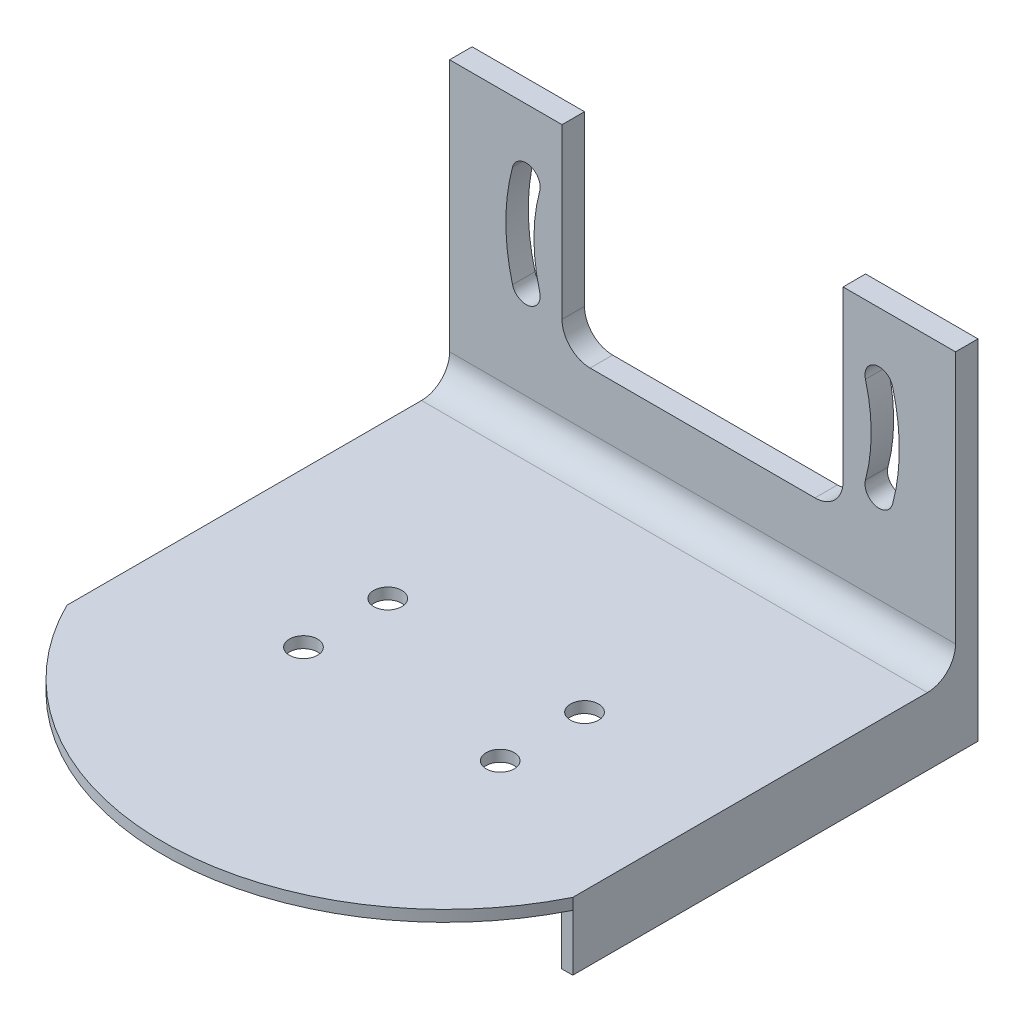
SolidWorks part; units mm, degrees
ref_plane "Front Plane" through (0, 0, 0) normal (0, 0, 1) x (1, 0, 0)
ref_plane "Top Plane" through (0, 0, 0) normal (0, 1, 0) x (1, 0, 0)
ref_plane "Right Plane" through (0, 0, 0) normal (1, 0, 0) x (0, 0, -1)
sketch "Sketch1" plane through (0, 0, 0) normal (0, 1, 0) x (1, 0, 0)
  line L1 (100, 50) -> (-100, 50)
  line L2 (100, 50) -> (100, -50)
  line L3 (100, -50) -> (-100, -50)
  line L4 (-100, 50) -> (-100, -50)
  line L5 (100, 50) -> (-100, -50) construction
  line L6 (100, -50) -> (-100, 50) construction
  point P0 (0, 0)
extrude "Boss-Extrude1" add sketch "Sketch1" along normal blind 2
sketch "Sketch3" plane through (0, 2, 0) normal (0, 1, 0) x (1, 0, 0)
  line L0 (0, 50) -> (-45, 50)
  line L1 (100, 50) -> (-100, 50) construction
  line L2 (0, 50) -> (45, 50)
  line L3 (45, 50) -> (45, 46)
  line L4 (-45, 50) -> (-45, 46)
  line L5 (-45, 46) -> (45, 46)
extrude "Boss-Extrude2" add sketch "Sketch3" along normal blind 50
sketch "Sketch4" plane through (0, 0, -50) normal (0, 0, -1) x (-1, 0, 0)
  line L0 (-45, 52) -> (-25, 52) construction
  line L1 (-45, 52) -> (45, 52) construction
  line L2 (45, 52) -> (25, 52) construction
  line L3 (25, 52) -> (25, 22)
  line L5 (-25, 22) -> (-25, 52)
  line L6 (-25, 52) -> (25, 52)
  line L7 (20, 17) -> (-20, 17)
  line L11 (25, 52) -> (-25, 52)
  arc A0 (-20, 17) -> (-25, 22) centre (-20, 22) cw
  arc A1 (20, 17) -> (25, 22) centre (20, 22) ccw
  dimension "D1" = 5
extrude "Cut-Extrude6" cut sketch "Sketch4" against normal blind 50
sketch "Sketch5" plane through (0, 0, -50) normal (0, 0, -1) x (-1, 0, 0)
  line L0 (-25, 52) -> (0, 52) construction
  line L1 (0, 52) -> (0, 32) construction
  line L2 (0, 32) -> (-17.2464, 32) construction
  line L3 (0, 32) -> (-28.9778, 39.7646) construction
  line L4 (-33.8074, 41.0587) -> (-39.8806, 42.686) construction
  arc A0 (-28.9778, 39.7646) -> (-28.9778, 24.2354) centre (0, 32) ccw
  arc A1 (-33.8074, 41.0587) -> (-33.8074, 22.9413) centre (0, 32) ccw
  arc A2 (-28.9778, 39.7646) -> (-33.8074, 41.0587) centre (-31.3926, 40.4116) ccw
  arc A3 (-28.9778, 24.2354) -> (-33.8074, 22.9413) centre (-31.3926, 23.5884) cw
  arc A4 (28.9778, 24.2354) -> (33.8074, 22.9413) centre (31.3926, 23.5884) ccw
  arc A5 (28.9778, 39.7646) -> (33.8074, 41.0587) centre (31.3926, 40.4116) cw
  arc A6 (28.9778, 24.2354) -> (28.9778, 39.7646) centre (0, 32) ccw
  arc A7 (33.8074, 22.9413) -> (33.8074, 41.0587) centre (0, 32) ccw
  dimension "D1" = 15
extrude "Cut-Extrude7" cut sketch "Sketch5" against normal blind 50
sketch "Sketch9" plane through (0, 2, 0) normal (0, 1, 0) x (1, 0, 0)
  line L0 (0, 0) -> (0, 7.5) construction
  line L1 (0, 7.5) -> (-17.5, 7.5) construction
  line L2 (0, 0) -> (-4.2264, 0) construction
  circle A0 centre (-17.5, 7.5) radius 2.5
  circle A1 centre (17.5, 7.5) radius 2.5
  circle A2 centre (17.5, -7.5) radius 2.5
  circle A3 centre (-17.5, -7.5) radius 2.5
extrude "Cut-Extrude8" cut sketch "Sketch9" against normal blind 20
sketch "Sketch17" plane through (0, 2, 0) normal (0, 1, 0) x (1, 0, 0)
  line L0 (-45, 50) -> (-45, -50)
  line L1 (45, 50) -> (45, -50)
  line L2 (-100, -50) -> (100, -50) construction
extrude "Cut-Extrude20" cut sketch "Sketch17" against normal through all and the other way through all
sketch "Sketch18" plane through (-45, 0, 0) normal (-1, 0, 0) x (0, 0, 1)
  line L2 (-46, 7) -> (-46, 2)
  line L3 (-46, 2) -> (-41, 2)
  arc A0 (-46, 7) -> (-41, 2) centre (-41, 7) ccw
  point P6 (-46, 2)
  dimension "D1" = 5
extrude "Boss-Extrude5" add sketch "Sketch18" against normal blind 90
sketch "Sketch24" plane through (0, 2, 0) normal (0, 1, 0) x (1, 0, 0)
  line L1 (-45, -50) -> (-45, 41) construction
  line L2 (45, -50) -> (45, 41) construction
  arc A0 (-45, -22.0935) -> (45, -22.0935) centre (0, 0.2351) ccw
extrude "Cut-Extrude28" cut sketch "Sketch24" against normal through all and the other way through all flip side to cut
sketch "Sketch25" plane through (0, 0, 0) normal (0, -1, 0) x (1, 0, 0)
  line L1 (-45, -50) -> (-43, -50)
  line L2 (-45, -50) -> (-45, 22.0935)
  line L3 (-45, 22.0935) -> (-43, 22.0935)
  line L4 (-43, -50) -> (-43, 22.0935)
  line L5 (45, -50) -> (43, -50)
  line L6 (45, -50) -> (45, 22.0935)
  line L7 (45, 22.0935) -> (43, 22.0935)
  line L8 (43, -50) -> (43, 22.0935)
extrude "Boss-Extrude7" add sketch "Sketch25" along normal blind 10
